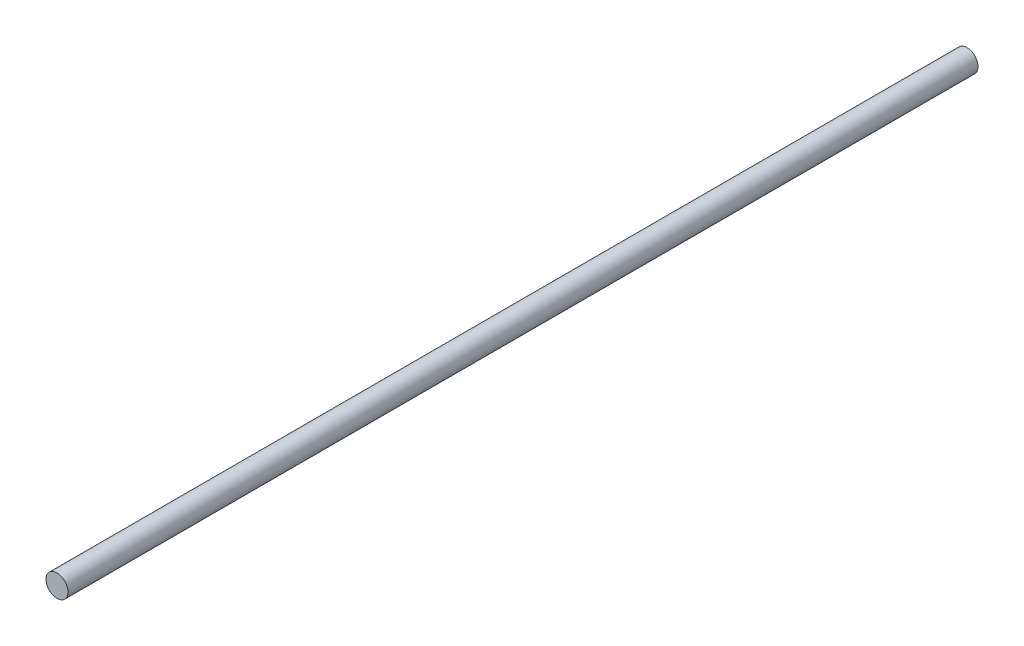
SolidWorks part; units mm, degrees
ref_plane "Front" through (0, 0, 0) normal (0, 0, 1) x (1, 0, 0)
ref_plane "Top" through (0, 0, 0) normal (0, 1, 0) x (1, 0, 0)
ref_plane "Right" through (0, 0, 0) normal (1, 0, 0) x (0, 0, -1)
sketch "Sketch1" plane through (0, 0, 0) normal (0, 0, 1) x (1, 0, 0)
  circle A0 centre (0, 0) radius 4
  dimension "D1" = 8
extrude "Boss-Extrude1" add sketch "Sketch1" along normal mid plane 330
